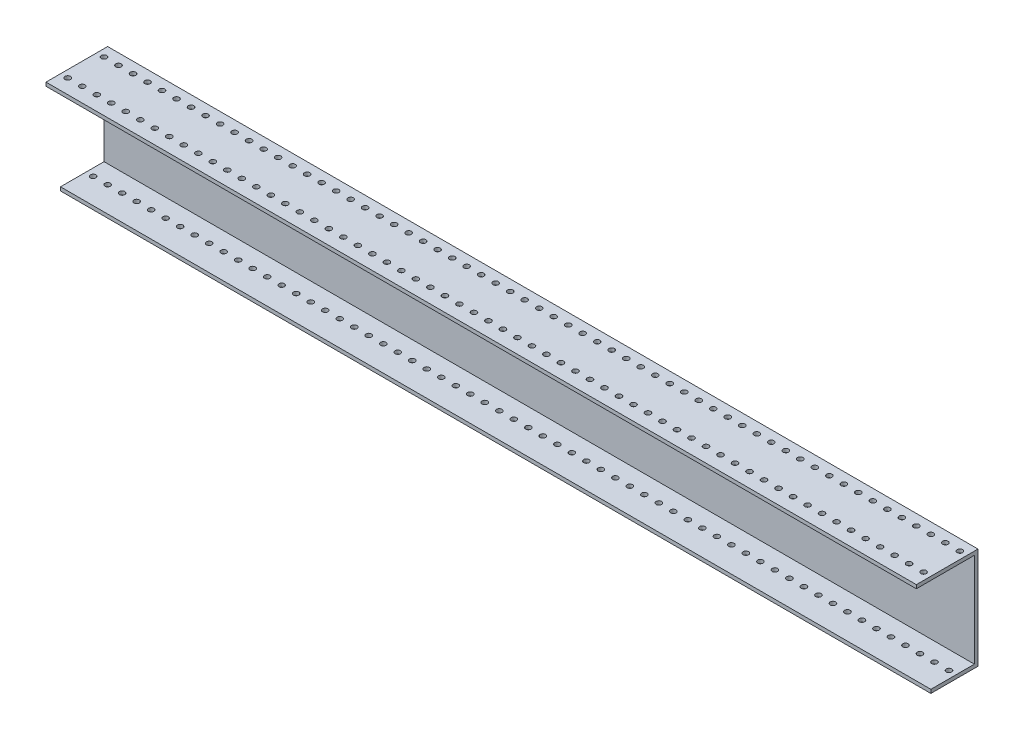
SolidWorks part; units mm, degrees
ref_plane "Front Plane" through (0, 0, 0) normal (0, 0, 1) x (1, 0, 0)
ref_plane "Top Plane" through (0, 0, 0) normal (0, 1, 0) x (1, 0, 0)
ref_plane "Right Plane" through (0, 0, 0) normal (1, 0, 0) x (0, 0, -1)
sketch "Sketch1" plane through (0, 0, 0) normal (0, 0, 1) x (1, 0, 0)
  line L1 (0, 0) -> (762, 0)
  line L2 (0, 0) -> (0, 88.9)
  line L3 (0, 88.9) -> (762, 88.9)
  line L4 (762, 0) -> (762, 88.9)
  dimension "D1" = 88.9
  dimension "D2" = 762
extrude "Boss-Extrude1" add sketch "Sketch1" along normal blind 3.175 contours L2 L1 L4 L3
sketch "Sketch2" plane through (0, 0, 3.175) normal (0, 0, 1) x (1, 0, 0)
  line L0 (762, 0) -> (762, 88.9) construction
  line L1 (0, 88.9) -> (762, 88.9)
  line L2 (0, 88.9) -> (0, 85.725)
  line L3 (0, 85.725) -> (762, 85.725)
  line L4 (762, 88.9) -> (762, 85.725)
  dimension "D1" = 3.175
extrude "Boss-Extrude2" add sketch "Sketch2" along normal blind 50.8 contours L2 L1 L4 L3
sketch "Sketch3" plane through (0, 0, 3.175) normal (0, 0, 1) x (1, 0, 0)
  line L0 (0, 0) -> (0, 85.725) construction
  line L1 (762, 0) -> (0, 0)
  line L2 (762, 0) -> (762, 3.175)
  line L3 (762, 3.175) -> (0, 3.175)
  line L4 (0, 0) -> (0, 3.175)
  dimension "D1" = 3.175
extrude "Boss-Extrude3" add sketch "Sketch3" along normal blind 38.1
sketch "Sketch4" plane through (0, 88.9, 0) normal (0, 1, 0) x (1, 0, 0)
  line L0 (740.1062, -53.975) -> (740.1062, -41.275) construction
  line L1 (0, -53.975) -> (762, -53.975) construction
  line L2 (762, -41.275) -> (755.65, -41.275) construction
  line L3 (762, -53.975) -> (762, 0) construction
  circle A0 centre (755.65, -41.275) radius 2.3812
  dimension "D1" = 12.7
  dimension "D2" = 6.35
extrude "Cut-Extrude1" cut sketch "Sketch4" against normal blind 3.175
ref_plane "Plane1" through (0, 0, 25.4) normal (0, 0, -1) x (-1, 0, 0)
mirror "Mirror1" about plane through (0, 0, 25.4) normal (0, 0, -1) of "Cut-Extrude1"
pattern_linear "LPattern1" count 60 spacing 12.7 along (-1, 0, 0) of "Mirror1", "Cut-Extrude1"
sketch "Sketch5" plane through (0, 0, 0) normal (0, -1, 0) x (-1, 0, 0)
  line L0 (0, -18.1491) -> (-6.35, -18.1491) construction
  line L1 (0, -41.275) -> (0, 0) construction
  line L2 (-6.35, 0) -> (-6.35, -19.05) construction
  line L3 (0, 0) -> (-762, 0) construction
  circle A0 centre (-6.35, -19.05) radius 2.3813
  dimension "D1" = 6.35
  dimension "D2" = 19.05
extrude "Cut-Extrude2" cut sketch "Sketch5" against normal blind 3.175
pattern_linear "LPattern3" count 60 spacing 12.7 along (1, 0, 0) of "Cut-Extrude2"
ref_plane "Plane9" through (0, 0, 374.65) normal (0, 0, -1) x (-1, 0, 0)
